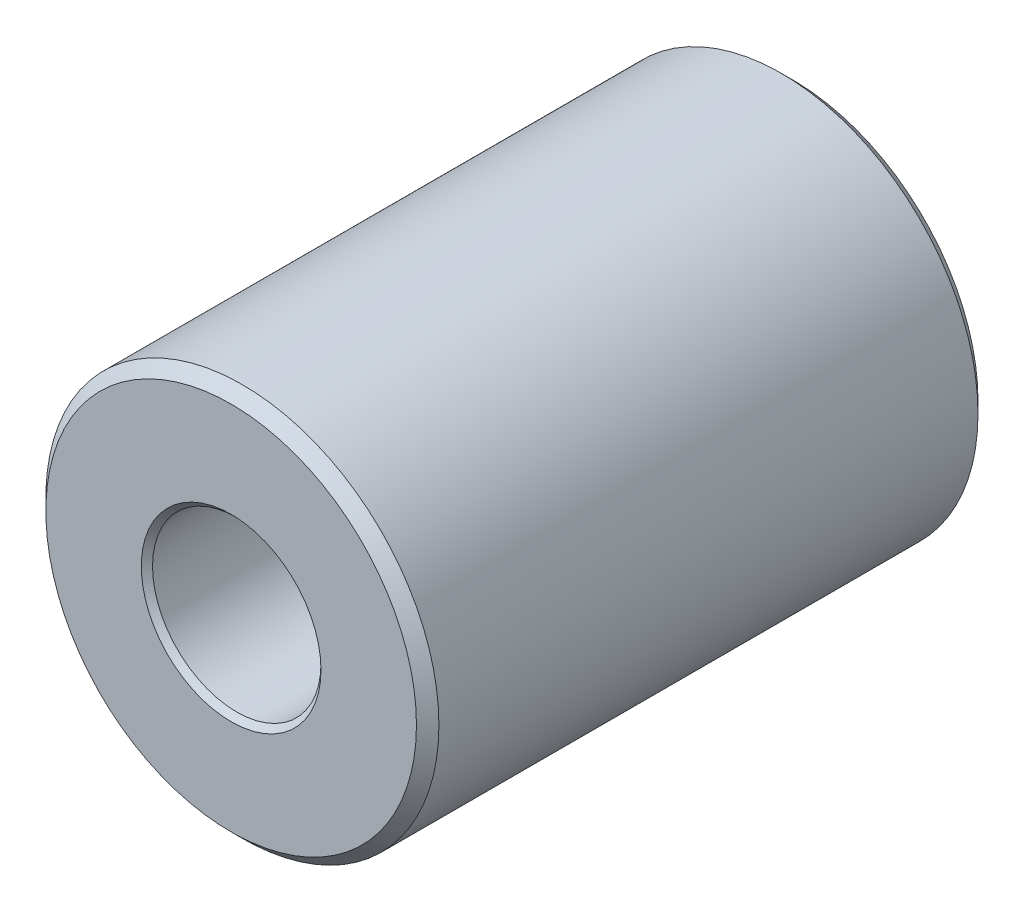
SolidWorks part; units mm, degrees
ref_plane "Front Plane" through (0, 0, 0) normal (0, 0, 1) x (1, 0, 0)
ref_plane "Top Plane" through (0, 0, 0) normal (0, 1, 0) x (1, 0, 0)
ref_plane "Right Plane" through (0, 0, 0) normal (1, 0, 0) x (0, 0, -1)
sketch "Sketch2" plane through (0, 0, 0) normal (0, 0, 1) x (1, 0, 0)
  circle A0 centre (6.0924, -11.1187) radius 3.5
  dimension "D1" = 7
extrude "Boss-Extrude1" add sketch "Sketch2" along normal blind 10
sketch "Sketch3" plane through (0, 0, 10) normal (0, 0, 1) x (1, 0, 0)
  circle A0 centre (6.0924, -11.1187) radius 1.5
  dimension "D1" = 3
extrude "Cut-Extrude1" cut sketch "Sketch3" against normal blind 10
chamfer "Chamfer1" distance 0.2 angle 45 2 edges at (9.5924, -11.1187, 0) (9.5924, -11.1187, 10)
chamfer "Chamfer2" distance 0.1 angle 45 2 edges at (7.5924, -11.1187, 10) (7.5924, -11.1187, 0)
